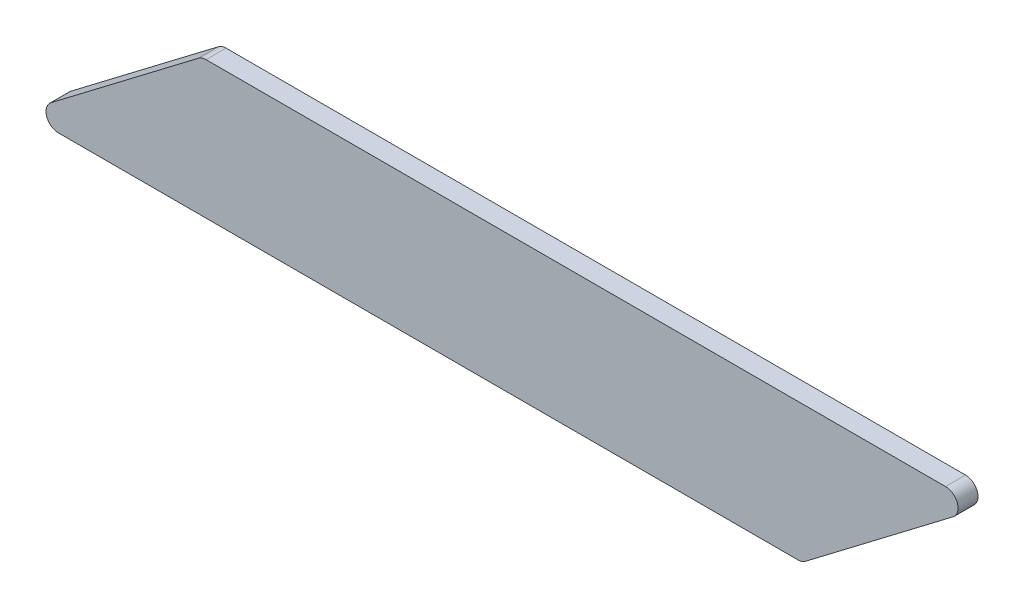
SolidWorks part; units mm, degrees
material "3003-H14"
ref_plane "X-Y Datum" through (0, 0, 0) normal (0, 0, 1) x (1, 0, 0)
ref_plane "X-Z Datum" through (0, 0, 0) normal (0, 1, 0) x (1, 0, 0)
ref_plane "Y-Z Datum" through (0, 0, 0) normal (1, 0, 0) x (0, 0, -1)
sketch "Sketch1" plane through (0, 0, 0) normal (0, 0, 1) x (1, 0, 0)
  line L1 (-38.5, -5.5) -> (38.5, -5.5)
  line L2 (-38.5, -5.5) -> (-38.5, 5.5)
  line L3 (-38.5, 5.5) -> (38.5, 5.5)
  line L4 (38.5, -5.5) -> (38.5, 5.5)
  line L5 (-38.5, -5.5) -> (38.5, 5.5) construction
  line L6 (-38.5, 5.5) -> (38.5, -5.5) construction
  point P0 (0, 0)
  dimension "D1" = 77
  dimension "D2" = 11
extrude "Boss-Extrude1" add sketch "Sketch1" along normal blind 1.6
sketch "Sketch2" plane through (0, 0, 1.6) normal (0, 0, 1) x (1, 0, 0)
  line L1 (-38.5, -5.5) -> (38.5, -5.5) construction
  line L2 (38.5, 5.5) -> (24.0455, -5.5)
  line L4 (38.5, 5.5) -> (-38.5, 5.5) construction
  line L5 (-38.5, -5.5) -> (-24.0455, 5.5)
extrude "Cut-Extrude1" cut sketch "Sketch2" against normal blind 10 and the other way through all
fillet "Fillet2" radius 1 4 edges at (24.0455, -5.5, 0.8) (38.5, 5.5, 0.8) (-24.0455, 5.5, 0.8) (-38.5, -5.5, 0.8)
